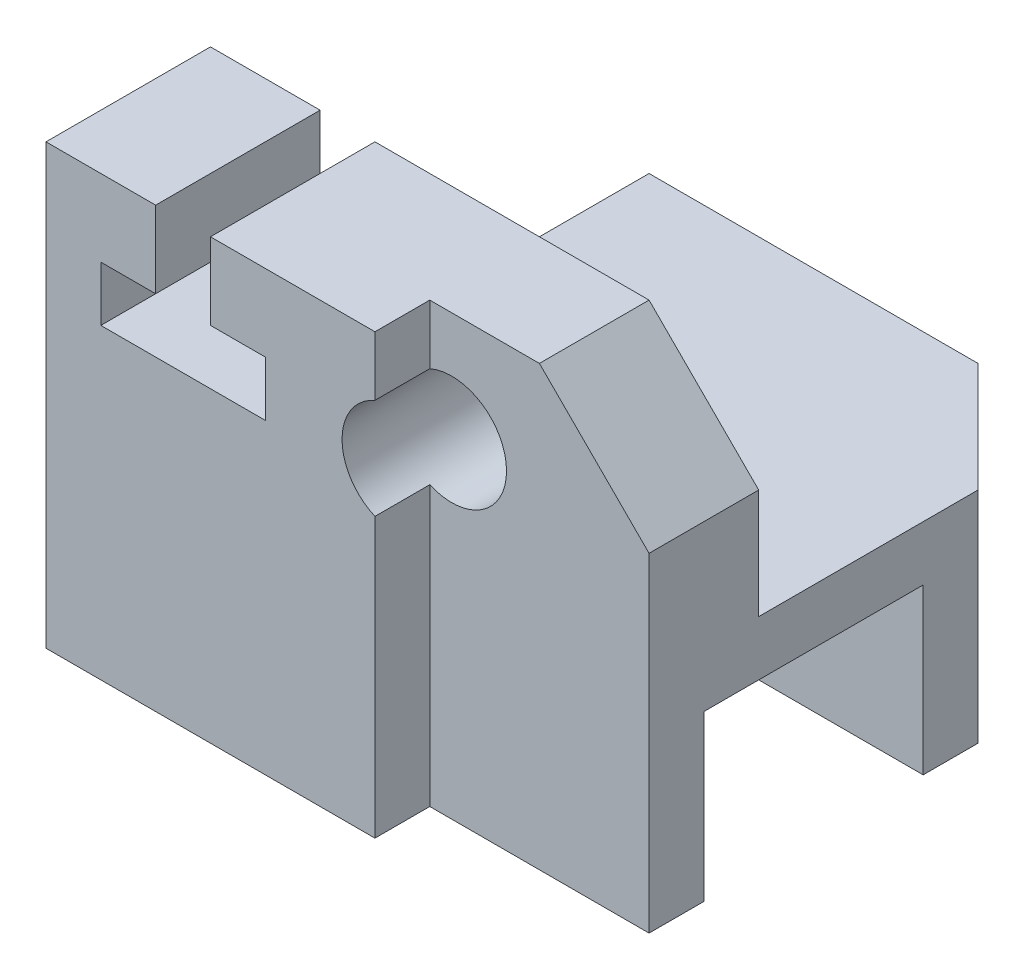
SolidWorks part; units mm, degrees
ref_plane "Plan de face" through (0, 0, 0) normal (0, 0, 1) x (1, 0, 0)
ref_plane "Plan de dessus" through (0, 0, 0) normal (0, 1, 0) x (1, 0, 0)
ref_plane "Plan de droite" through (0, 0, 0) normal (1, 0, 0) x (0, 0, -1)
sketch "Esquisse3" plane through (0, 0, 0) normal (0, 0, 1) x (1, 0, 0)
  line L1 (-89.1834, -54.8454) -> (-39.1834, -54.8454)
  line L2 (-89.1834, -54.8454) -> (-89.1834, -14.8454)
  line L3 (-89.1834, -14.8454) -> (-39.1834, -14.8454)
  line L4 (-39.1834, -54.8454) -> (-39.1834, -14.8454)
extrude "Boss.-Extru.1" add sketch "Esquisse3" along normal mid plane 45
sketch "Esquisse7" plane through (-39.1834, 0, 0) normal (1, 0, 0) x (0, 0, -1)
  line L1 (22.5, -14.8454) -> (-7.5, -14.8454)
  line L2 (22.5, -14.8454) -> (22.5, -34.8454)
  line L3 (22.5, -34.8454) -> (-7.5, -34.8454)
  line L4 (-7.5, -14.8454) -> (-7.5, -34.8454)
  dimension "D1" = 30
  dimension "D2" = 20
extrude "Enlèv. mat.-Extru.1" cut sketch "Esquisse7" against normal through all
sketch "Esquisse8" plane through (-39.1834, 0, 0) normal (1, 0, 0) x (0, 0, -1)
  line L0 (-22.5, -54.8454) -> (22.5, -54.8454) construction
  line L1 (-22.5, -14.8454) -> (-17.5, -14.8454)
  line L2 (-22.5, -14.8454) -> (-22.5, -54.8454)
  line L3 (-22.5, -54.8454) -> (-17.5, -54.8454)
  line L4 (-17.5, -14.8454) -> (-17.5, -54.8454)
extrude "Enlèv. mat.-Extru.2" cut sketch "Esquisse8" against normal blind 20
sketch "Esquisse9" plane through (-89.1834, 0, 0) normal (-1, 0, 0) x (0, 0, 1)
  line L1 (-22.5, -34.8454) -> (-7.5, -34.8454)
  line L2 (-22.5, -34.8454) -> (-22.5, -44.8454)
  line L3 (-22.5, -44.8454) -> (-7.5, -44.8454)
  line L4 (-7.5, -34.8454) -> (-7.5, -44.8454)
extrude "Enlèv. mat.-Extru.3" cut sketch "Esquisse9" against normal blind 10
chamfer "Chanfrein2" distance 10 angle 45 1 edges at (-39.1834, -14.8454, 12.5)
chamfer "Chanfrein3" distance 10 angle 45 1 edges at (-39.1834, -44.8454, -22.5)
sketch "Esquisse10" plane through (0, 0, 7.5) normal (0, 0, -1) x (-1, 0, 0)
  line L0 (89.1834, -14.8454) -> (49.1834, -14.8454) construction
  line L1 (74.1834, -14.8454) -> (79.1834, -14.8454)
  line L2 (74.1834, -14.8454) -> (74.1834, -21.8454)
  line L4 (79.1834, -14.8454) -> (79.1834, -21.8454)
  line L5 (69.1834, -21.8454) -> (74.1834, -21.8454)
  line L7 (69.1834, -21.8454) -> (69.1834, -26.8454)
  line L8 (69.1834, -26.8454) -> (84.1834, -26.8454)
  line L9 (84.1834, -21.8454) -> (84.1834, -26.8454)
  line L10 (79.1834, -21.8454) -> (84.1834, -21.8454)
  dimension "D1" = 10
  dimension "D2" = 5
  dimension "D3" = 5
  dimension "D4" = 5
  dimension "D5" = 5
  dimension "D6" = 7
extrude "Enlèv. mat.-Extru.4" cut sketch "Esquisse10" against normal through all
sketch "Esquisse11" plane through (-39.1834, 0, 0) normal (1, 0, 0) x (0, 0, -1)
  line L0 (-17.5, -54.8454) -> (12.5, -54.8454) construction
  line L1 (-12.5, -54.8454) -> (7.5, -54.8454)
  line L2 (-12.5, -54.8454) -> (-12.5, -39.8454)
  line L3 (-12.5, -39.8454) -> (7.5, -39.8454)
  line L4 (7.5, -54.8454) -> (7.5, -39.8454)
  dimension "D1" = 20
  dimension "D2" = 15
  dimension "D3" = 5
extrude "Enlèv. mat.-Extru.5" cut sketch "Esquisse11" against normal blind 25
sketch "Esquisse12" plane through (0, 0, -22.5) normal (0, 0, -1) x (-1, 0, 0)
  line L0 (89.1834, -54.8454) -> (49.1834, -54.8454) construction
  line L1 (54.1834, -54.8454) -> (64.1834, -54.8454)
  line L2 (54.1834, -54.8454) -> (54.1834, -39.8454)
  line L3 (54.1834, -39.8454) -> (64.1834, -39.8454)
  line L4 (64.1834, -54.8454) -> (64.1834, -39.8454)
  dimension "D1" = 15
  dimension "D2" = 10
  dimension "D3" = 5
extrude "Enlèv. mat.-Extru.6" cut sketch "Esquisse12" against normal blind 25
sketch "Esquisse14" plane through (0, -34.8454, 0) normal (0, 1, 0) x (1, 0, 0)
  line L0 (-79.1834, 22.5) -> (-49.1834, 22.5) construction
  line L1 (-89.1834, -7.5) -> (-89.1834, 7.5) construction
  circle A0 centre (-74.1834, 3.5) radius 3
  point P2 (0, 0)
  point P3 (0, 0)
  dimension "D3" = 6
  dimension "D1" = 19
  dimension "D2" = 15
extrude "Enlèv. mat.-Extru.7" cut sketch "Esquisse14" against normal through all
sketch "Esquisse15" plane through (0, 0, 7.5) normal (0, 0, -1) x (-1, 0, 0)
  line L0 (74.1834, -14.8454) -> (49.1834, -14.8454) construction
  line L2 (39.1834, -24.8454) -> (39.1834, -34.8454) construction
  circle A0 centre (57.1834, -24.8454) radius 5
  point P2 (0, 0)
  point P5 (0, 0)
  point P7 (57.1834, -26.8454)
  point P8 (0, 0)
  dimension "D3" = 10
  dimension "D1" = 10
  dimension "D2" = 18
extrude "Enlèv. mat.-Extru.8" cut sketch "Esquisse15" against normal through all
